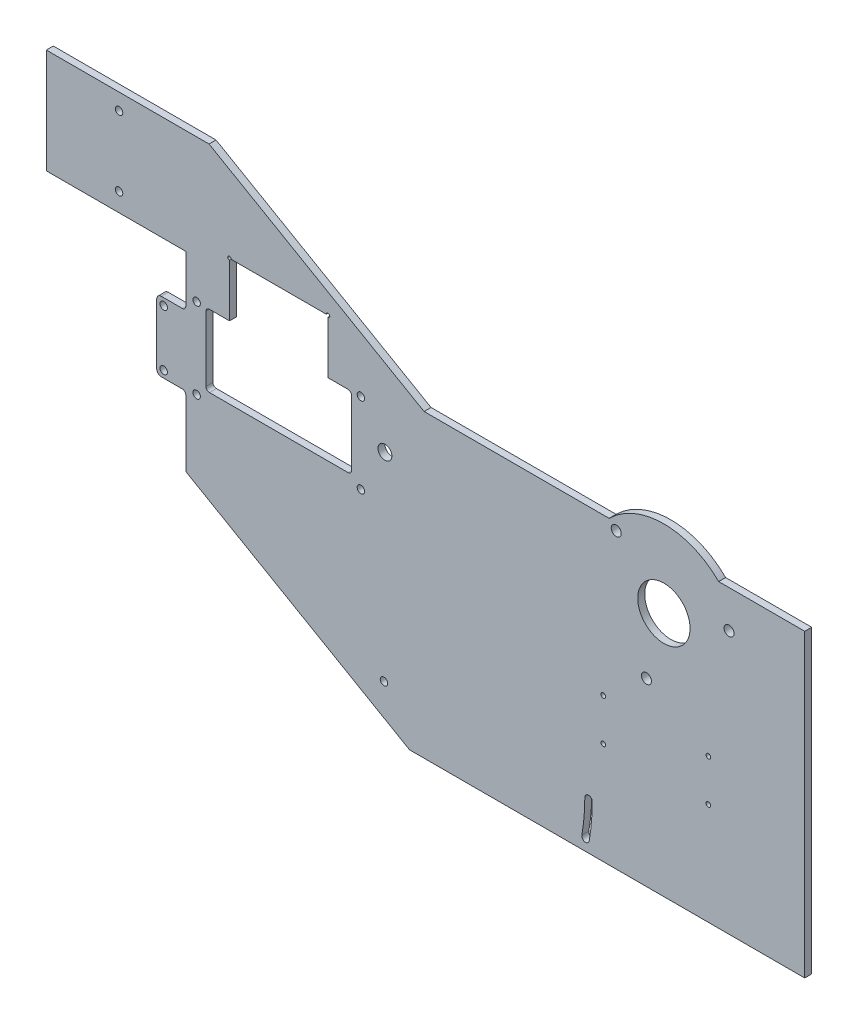
SolidWorks part; units mm, degrees
material "Thornel Mat VMA"
ref_plane "Front Plane" through (0, 0, 0) normal (0, 0, 1) x (1, 0, 0)
ref_plane "Top Plane" through (0, 0, 0) normal (0, 1, 0) x (1, 0, 0)
ref_plane "Right Plane" through (0, 0, 0) normal (1, 0, 0) x (0, 0, -1)
sketch "Sketch1" plane through (0, 0, 0) normal (0, 0, 1) x (1, 0, 0)
  line L1 (20.2869, 47.6) -> (204.7012, 47.6)
  line L2 (20.2869, 47.6) -> (20.2869, -36.0143)
  line L3 (20.2869, -36.0143) -> (204.7012, -36.0143)
  line L4 (204.7012, 47.6) -> (204.7012, -36.0143)
extrude "Boss-Extrude1" add sketch "Sketch1" along normal blind 3
sketch "Sketch2" plane through (0, 0, 0) normal (0, 0, -1) x (-1, 0, 0)
  circle A0 centre (-24.1169, 24) radius 3
  dimension "D1" = 6
extrude "Cut-Extrude1" cut sketch "Sketch2" against normal blind 70
sketch "Sketch3" plane through (0, 0, 3) normal (0, 0, 1) x (1, 0, 0)
  line L0 (24.1169, 24) -> (144.1169, 24) construction
  circle A0 centre (144.1169, 24) radius 11.25
  dimension "D2" = 22.5
  dimension "D1" = 120
extrude "Cut-Extrude2" cut sketch "Sketch3" against normal blind 3
sketch "Sketch4" plane through (0, 0, 3) normal (0, 0, 1) x (1, 0, 0)
  line L0 (-61.5431, 47.6) -> (-61.5431, -3) construction
  line L1 (-61.5431, 56) -> (-61.5431, 34)
  line L2 (-61.5431, 4) -> (-61.5431, -26)
  line L3 (-61.5431, 34) -> (-72.0431, 34)
  line L5 (-61.5431, 4) -> (-72.0431, 4)
  line L6 (-74.0431, 32) -> (-74.0431, 6)
  line L7 (-51.5431, 101) -> (-121.5431, 101)
  line L8 (-121.5431, 101) -> (-121.5431, 56)
  line L9 (-121.5431, 56) -> (-61.5431, 56)
  line L10 (-51.5431, 101) -> (40.9484, 47.6)
  line L11 (20.2869, 47.6) -> (20.2869, -36.0143)
  line L12 (20.2869, -36.0143) -> (204.7012, -36.0143)
  line L13 (204.7012, -36.0143) -> (204.7012, 47.6)
  line L14 (204.7012, 47.6) -> (20.2869, 47.6)
  line L15 (20.2869, 47.6) -> (20.2869, -36.0143)
  line L16 (20.2869, -36.0143) -> (204.7012, -36.0143)
  line L18 (40.9484, 47.6) -> (20.2869, 47.6)
  line L19 (-61.5431, -26) -> (34.7012, -81.5667)
  line L20 (34.7012, -81.5667) -> (204.7012, -81.5667)
  line L21 (204.7012, -81.5667) -> (204.7012, -36.0143)
  line L22 (-85.0431, 56) -> (-64.7431, 56) construction
  circle A0 centre (-71.0431, 31) radius 1.6
  circle A1 centre (-71.0431, 7) radius 1.6
  arc A2 (-72.0431, 4) -> (-74.0431, 6) centre (-72.0431, 6) cw
  arc A3 (-72.0431, 34) -> (-74.0431, 32) centre (-72.0431, 32) ccw
  dimension "D1" = 3.2
  dimension "D2" = 3
  dimension "D5" = 2
  dimension "D3" = 3
  dimension "D4" = 3
  dimension "D7" = 60
  dimension "D8" = 45
  dimension "D9" = 30
  dimension "D10" = 30
  dimension "D11" = 70
  dimension "D12" = 170
  dimension "D6" = 0
extrude "Boss-Extrude2" add sketch "Sketch4" against normal blind 3
sketch "Sketch5" plane through (0, 0, 3) normal (0, 0, 1) x (1, 0, 0)
  line L0 (-0.5431, 62.6) -> (-42.5431, 62.6) construction
  line L1 (8.2869, 8.5) -> (-51.3731, 8.5)
  line L2 (9.7869, 10) -> (9.7869, 38)
  line L3 (8.2869, 39.5) -> (-0.3431, 39.5)
  line L4 (-52.8731, 10) -> (-52.8731, 38)
  line L5 (-41.9931, 62.8) -> (-1.0931, 62.8)
  line L6 (-42.7431, 62.05) -> (-42.7431, 39.5)
  line L8 (-0.3431, 62.05) -> (-0.3431, 39.5)
  line L9 (-42.5431, 57.6) -> (-42.5431, 52.6) construction
  line L10 (-0.5431, 62.6) -> (-0.5431, 57.6) construction
  line L11 (-42.7431, 39.5) -> (-51.3731, 39.5)
  line L13 (7.7869, 47.6) -> (7.7869, -3) construction
  line L14 (-50.8731, -3) -> (-50.8731, 47.6) construction
  line L15 (8.4569, 34.5) -> (-51.5431, 34.5) construction
  line L16 (-51.5431, 13.5) -> (8.4569, 13.5) construction
  arc A0 (9.7869, 38) -> (8.2869, 39.5) centre (8.2869, 38) ccw
  arc A1 (8.2869, 8.5) -> (9.7869, 10) centre (8.2869, 10) ccw
  arc A2 (-51.3731, 8.5) -> (-52.8731, 10) centre (-51.3731, 10) cw
  arc A3 (-51.3731, 39.5) -> (-52.8731, 38) centre (-51.3731, 38) ccw
  arc A4 (-41.9931, 62.8) -> (-42.7431, 62.05) centre (-42.7431, 62.8) ccw
  arc A6 (-1.0931, 62.8) -> (-0.3431, 62.05) centre (-0.3431, 62.8) cw
  dimension "D8" = 1.5
  dimension "D9" = 1.5
  dimension "D10" = 0.75
  dimension "D1" = 0.2
  dimension "D2" = 0.2
  dimension "D3" = 0.2
  dimension "D4" = 2
  dimension "D5" = 2
  dimension "D6" = 5
  dimension "D7" = 5
extrude "Cut-Extrude3" cut sketch "Sketch5" against normal blind 10 contours L8 L5 L6 L3 | L4 L1 L2 L3
sketch "Sketch6" plane through (0, 0, 3) normal (0, 0, 1) x (1, 0, 0)
  line L0 (-61.5431, -3) -> (-50.8731, -3) construction
  line L1 (13.7869, 5) -> (-56.8731, 5) construction
  line L2 (13.7869, 5) -> (13.7869, 39.6) construction
  line L3 (13.7869, 39.6) -> (-56.8731, 39.6) construction
  line L4 (-56.8731, 5) -> (-56.8731, 39.6) construction
  line L5 (-61.5431, 47.6) -> (-50.8731, 47.6) construction
  line L6 (-52.8731, 10) -> (-52.8731, 38) construction
  line L7 (9.7869, 10) -> (9.7869, 38) construction
  circle A0 centre (13.7869, 5) radius 1.6
  circle A1 centre (13.7869, 39.6) radius 1.6
  circle A2 centre (-56.8731, 5) radius 1.6
  circle A3 centre (-56.8731, 39.6) radius 1.6
  dimension "D5" = 3.2
  dimension "D1" = 8
  dimension "D2" = 8
  dimension "D3" = 4
  dimension "D4" = 4
extrude "Cut-Extrude4" cut sketch "Sketch6" against normal blind 3
fillet "Fillet1" radius 1.5 2 edges at (-61.5431, 4, 1.5) (-61.5431, 34, 1.5)
sketch "Sketch8" plane through (0, 0, 3) normal (0, 0, 1) x (1, 0, 0)
  circle A0 centre (-90.2431, 94) radius 1.6
  circle A1 centre (-90.2431, 64) radius 1.6
  dimension "D1" = 3.2
extrude "Cut-Extrude6" cut sketch "Sketch8" against normal blind 12
sketch "Sketch9" plane through (0, 0, 0) normal (0, 0, -1) x (-1, 0, 0)
  circle A0 centre (-172.1287, 31.5058) radius 2.15
  circle A1 centre (-123.6108, 44.5061) radius 2.15
  circle A2 centre (-136.6111, -4.0118) radius 2.15
  dimension "D1" = 4.3
extrude "Cut-Extrude7" cut sketch "Sketch9" against normal blind 12
sketch "Sketch10" plane through (0, 0, 0) normal (0, 0, -1) x (-1, 0, 0)
  line L0 (-204.7012, 47.6) -> (-40.9484, 47.6) construction
  line L1 (-167.6809, 47.6) -> (-120.5529, 47.6)
  arc A0 (-120.5529, 47.6) -> (-167.6809, 47.6) centre (-144.1169, 24) ccw
  dimension "D1" = 66.7
extrude "Boss-Extrude3" add sketch "Sketch10" against normal blind 3
sketch "Sketch12" plane through (0, 0, 3) normal (0, 0, 1) x (1, 0, 0)
  line L0 (34.7012, -81.5667) -> (204.7012, -81.5667) construction
  circle A0 centre (23.7012, -61.5667) radius 1.6
  arc A1 (111.7012, -61.5667) -> (110.4134, -76.5667) centre (23.7012, -61.5667) cw construction
  arc A2 (110.1012, -61.5667) -> (108.8368, -76.294) centre (23.7012, -61.5667) cw
  arc A3 (113.3012, -61.5667) -> (111.99, -76.8394) centre (23.7012, -61.5667) cw
  arc A4 (113.3012, -61.5667) -> (110.1012, -61.5667) centre (111.7012, -61.5667) ccw
  arc A5 (111.99, -76.8394) -> (108.8368, -76.294) centre (110.4134, -76.5667) cw
  dimension "D1" = 3.2
  dimension "D2" = 1.6
  dimension "D3" = 5
extrude "Cut-Extrude8" cut sketch "Sketch12" against normal blind 10
sketch "Sketch13" plane through (0, 0, 0) normal (0, 0, -1) x (-1, 0, 0)
  circle A0 centre (-163.2569, -19.6667) radius 1
  circle A1 centre (-163.2569, -37.6667) radius 1
  circle A2 centre (-118.0569, -19.6667) radius 1
  circle A3 centre (-118.0569, -37.6667) radius 1
  dimension "D1" = 2
extrude "Cut-Extrude9" cut sketch "Sketch13" against normal blind 10
